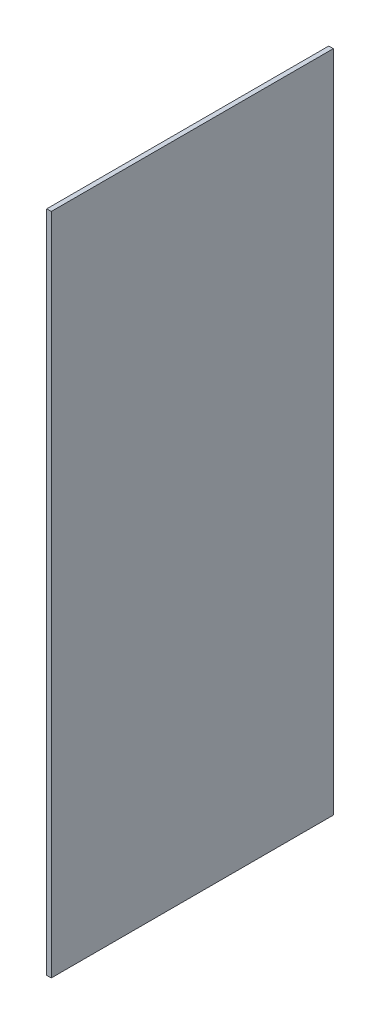
SolidWorks part; units mm, degrees
ref_plane "Front Plane" through (0, 0, 0) normal (0, 0, 1) x (1, 0, 0)
ref_plane "Top Plane" through (0, 0, 0) normal (0, 1, 0) x (1, 0, 0)
ref_plane "Right Plane" through (0, 0, 0) normal (1, 0, 0) x (0, 0, -1)
sketch "Sketch1" plane through (0, 0, 0) normal (1, 0, 0) x (0, 0, -1)
  line L1 (0, 0) -> (-196.088, 0)
  line L2 (0, 0) -> (0, 461.518)
  line L3 (0, 461.518) -> (-196.088, 461.518)
  line L4 (-196.088, 0) -> (-196.088, 461.518)
  dimension "D1" = 461.518
  dimension "D2" = 196.088
extrude "Boss-Extrude1" add sketch "Sketch1" along normal blind 3.175
